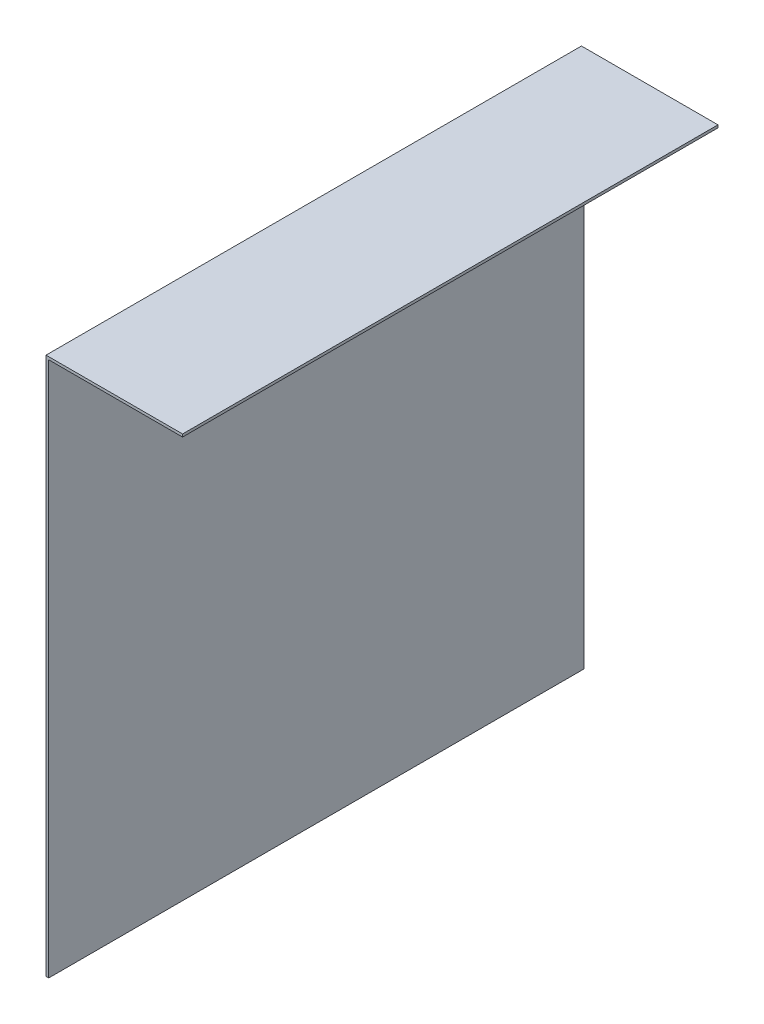
SolidWorks part; units mm, degrees
ref_plane "Alzado" through (0, 0, 0) normal (0, 0, 1) x (1, 0, 0)
ref_plane "Planta" through (0, 0, 0) normal (0, 1, 0) x (1, 0, 0)
ref_plane "Vista lateral" through (0, 0, 0) normal (1, 0, 0) x (0, 0, -1)
sketch "Croquis1" plane through (0, 0, 0) normal (0, 0, 1) x (1, 0, 0)
  line L0 (0, 0) -> (0, 600)
  line L1 (0, 600) -> (150, 600)
  line L2 (-3, 0) -> (-3, 603)
  line L3 (-3, 603) -> (150, 603)
  line L4 (0, 0) -> (-3, 0)
  line L5 (150, 600) -> (150, 603)
  dimension "D1" = 3
extrude "Saliente-Extruir1" add sketch "Croquis1" along normal blind 600
